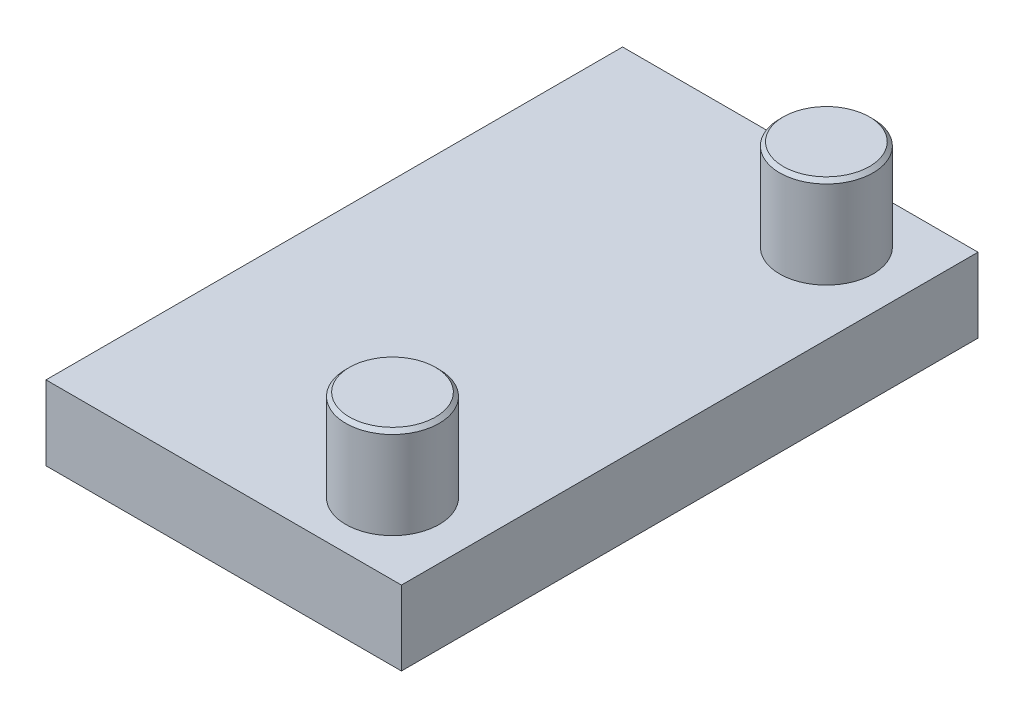
SolidWorks part; units mm, degrees
ref_plane "Front Plane" through (0, 0, 0) normal (0, 0, 1) x (1, 0, 0)
ref_plane "Top Plane" through (0, 0, 0) normal (0, 1, 0) x (1, 0, 0)
ref_plane "Right Plane" through (0, 0, 0) normal (1, 0, 0) x (0, 0, -1)
sketch "Sketch1" plane through (0, 0, 0) normal (0, 1, 0) x (1, 0, 0)
  line L0 (0, 5.4327) -> (0, 0) construction
  line L1 (0, 0) -> (4.9176, 0) construction
  line L2 (-6.1849, 10.033) -> (-6.1849, -10.033)
  line L3 (-6.1849, -10.033) -> (6.1849, -10.033)
  line L4 (6.1849, -10.033) -> (6.1849, 10.033)
  line L5 (6.1849, 10.033) -> (-6.1849, 10.033)
  dimension "D1" = 20.066
  dimension "D2" = 12.3698
extrude "Boss-Extrude1" add sketch "Sketch1" along normal blind 2.5908 contours L5 L2 L3 L4
sketch "Sketch2" plane through (0, 2.5908, 0) normal (0, 1, 0) x (1, 0, 0)
  line L0 (0, 10.033) -> (0, -10.033) construction
  line L1 (6.1849, 10.033) -> (-6.1849, 10.033) construction
  line L2 (-6.1849, -10.033) -> (6.1849, -10.033) construction
  line L3 (-6.1849, 0) -> (6.1849, 0) construction
  line L4 (-6.1849, 10.033) -> (-6.1849, -10.033) construction
  line L5 (6.1849, -10.033) -> (6.1849, 10.033) construction
  circle A0 centre (3.3909, 7.5502) radius 1.6256
  circle A1 centre (3.3909, -7.5501) radius 1.6256
  dimension "D4" = 3.2512
extrude "Boss-Extrude2" add sketch "Sketch2" along normal blind 3.175
chamfer "Chamfer1" distance 0.127 angle 45 2 edges at (3.3909, 5.7658, 5.9246) (3.3909, 5.7658, -5.9246)
